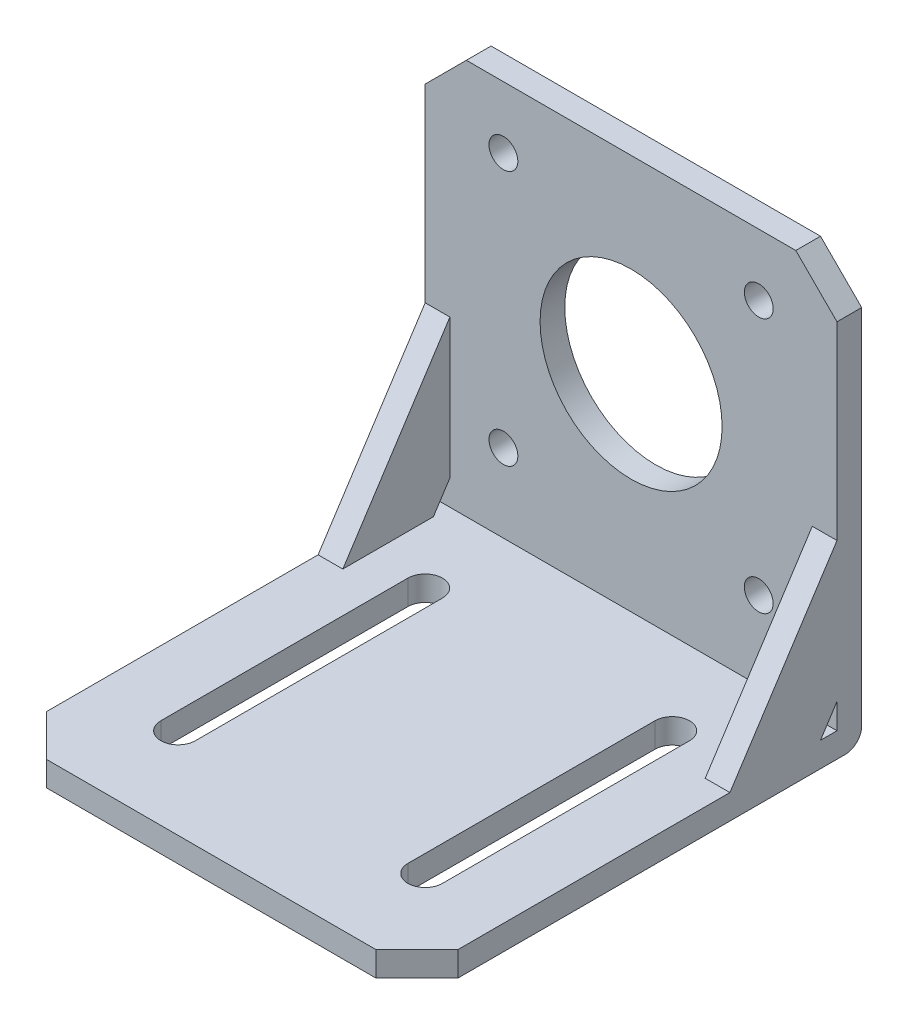
SolidWorks part; units mm, degrees
ref_plane "前视基准面" through (0, 0, 0) normal (0, 0, 1) x (1, 0, 0)
ref_plane "上视基准面" through (0, 0, 0) normal (0, 1, 0) x (1, 0, 0)
ref_plane "右视基准面" through (0, 0, 0) normal (1, 0, 0) x (0, 0, -1)
sketch "草图1" plane through (0, 0, 0) normal (0, 0, 1) x (1, 0, 0)
  line L0 (25, 29.7087) -> (25, -16.2913)
  line L1 (25, -16.2913) -> (-25, -16.2913)
  line L2 (-25, -16.2913) -> (-25, 29.7087)
  line L3 (-20, 34.7087) -> (20, 34.7087)
  line L4 (-25, 29.7087) -> (-20, 34.7087)
  line L5 (20, 34.7087) -> (25, 29.7087)
  line L6 (0, 11.7087) -> (0, 42.19) construction
  circle A0 centre (-15.5, 27.2087) radius 1.75
  circle A1 centre (15.5, 27.2087) radius 1.75
  circle A2 centre (-15.5, -3.7913) radius 1.75
  circle A3 centre (15.5, -3.7913) radius 1.75
  circle A4 centre (0, 11.7087) radius 11.05
  point P0 (25, 34.7087)
  point P3 (-25, 34.7087)
  dimension "D5" = 3.5
  dimension "D6" = 22.1
  dimension "D1" = 51
  dimension "D2" = 50
  dimension "D3" = 31
  dimension "D4" = 25
  dimension "D7" = 9.5
  dimension "D8" = 9.5
  dimension "D9" = 28
  dimension "D10" = 15.5
  dimension "D11" = 15.5
  dimension "D12" = 15.5
  dimension "D13" = 15.5
  dimension "D14" = 31
extrude "凸台-拉伸1" add sketch "草图1" along normal blind 3
sketch "草图2" plane through (0, 0, 3) normal (0, 0, 1) x (1, 0, 0)
  line L0 (-25, -13.2913) -> (25, -13.2913)
  line L1 (-25, 29.7087) -> (-25, -16.2913) construction
  line L2 (25, -16.2913) -> (25, 29.7087) construction
  line L3 (-25, -16.2913) -> (25, -16.2913) construction
  line L10 (-25, -16.2913) -> (25, -16.2913)
  line L11 (25, -16.2913) -> (25, 29.7087)
  line L12 (25, 29.7087) -> (20, 34.7087)
  line L13 (20, 34.7087) -> (-20, 34.7087)
  line L14 (-20, 34.7087) -> (-25, 29.7087)
  line L15 (-25, 29.7087) -> (-25, -16.2913)
  line L16 (-25, -16.2913) -> (25, -16.2913)
  line L17 (25, -16.2913) -> (25, -13.2913)
  line L21 (-25, -13.2913) -> (-25, -16.2913)
  dimension "D1" = 3
  dimension "D2" = 0
extrude "凸台-拉伸2" add sketch "草图2" along normal blind 51
fillet "圆角1" radius 2 1 edges at (0, -16.2913, 0)
sketch "草图3" plane through (0, -13.2913, 0) normal (0, 1, 0) x (1, 0, 0)
  line L0 (-17.1, -13) -> (-17.1, -43)
  line L1 (25, -54) -> (-25, -54) construction
  line L2 (-12.9, -43) -> (-12.9, -13)
  line L3 (12.9, -13) -> (12.9, -43)
  line L4 (17.1, -13) -> (17.1, -43)
  line L5 (25, -54) -> (25, -3) construction
  line L7 (-25, -54) -> (-25, -3) construction
  arc A0 (-12.9, -13) -> (-17.1, -13) centre (-15, -13) ccw
  arc A1 (17.1, -13) -> (12.9, -13) centre (15, -13) ccw
  arc A2 (12.9, -43) -> (17.1, -43) centre (15, -43) ccw
  arc A3 (-17.1, -43) -> (-12.9, -43) centre (-15, -43) ccw
  dimension "D1" = 4.2
  dimension "D2" = 30
  dimension "D3" = 11
  dimension "D4" = 10
  dimension "D5" = 30
  dimension "D6" = 10
extrude "切除-拉伸1" cut sketch "草图3" against normal blind 51
chamfer "倒角1" distance 5 angle 45 2 edges at (-25, -14.7913, 54) (25, -14.7913, 54)
sketch "草图4" plane through (25, 0, 0) normal (1, 0, 0) x (0, 0, -1)
  line L0 (-3, 6.7087) -> (-16, -13.2913)
  line L1 (-3, -13.2913) -> (-3, 29.7087) construction
  line L2 (-49, -13.2913) -> (-3, -13.2913) construction
  line L3 (-16, -13.2913) -> (-5, -13.2913)
  line L4 (-5, -13.2913) -> (-3, -10.2144)
  line L5 (-3, -10.2144) -> (-3, 6.7087)
  dimension "D1" = 20
  dimension "D2" = 13
  dimension "D3" = 2
extrude "凸台-拉伸3" add sketch "草图4" against normal blind 3
mirror "镜向1" about plane through (0, 0, 0) normal (1, 0, 0) of "凸台-拉伸3", "凸台-拉伸1"
fillet "圆角3" radius 2 1 edges at (0, -16.2913, 0)
